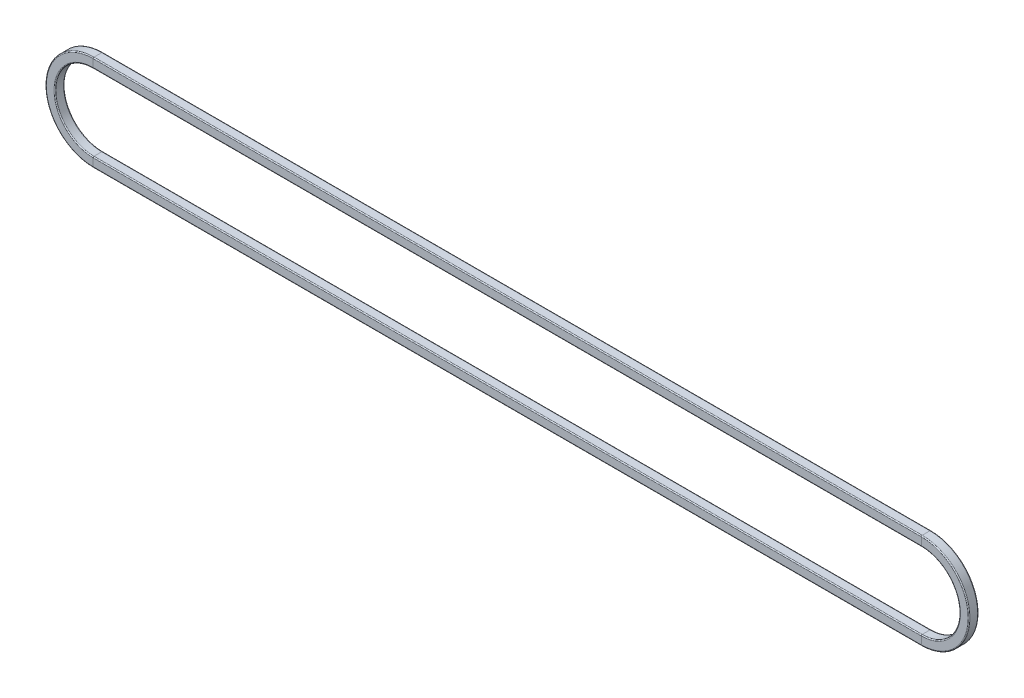
SolidWorks part; units mm, degrees
ref_plane "Front Plane" through (0, 0, 0) normal (0, 0, 1) x (1, 0, 0)
ref_plane "Top Plane" through (0, 0, 0) normal (0, 1, 0) x (1, 0, 0)
ref_plane "Right Plane" through (0, 0, 0) normal (1, 0, 0) x (0, 0, -1)
sketch "Sketch2" plane through (0, 0, 0) normal (0, 0, 1) x (1, 0, 0)
  line L0 (0, 0) -> (1, 0) construction
  line L1 (0, 0) -> (0, 1) construction
  line L2 (0, 4.5) -> (86.8, 4.5)
  line L3 (86.8, -4.5) -> (0, -4.5)
  arc A0 (0, -4.5) -> (0, 4.5) centre (0, 0) cw
  arc A1 (86.8, 4.5) -> (86.8, -4.5) centre (86.8, 0) cw
sketch "Sketch3" plane through (0, 0, 0) normal (1, 0, 0) x (0, 0, -1)
  line L0 (0, 4.5) -> (0, -4.5) construction
  line L1 (-0.5, 5) -> (0.5, 5)
  line L2 (-0.5, 5) -> (-0.5, 4)
  line L3 (-0.5, 4) -> (0.5, 4)
  line L4 (0.5, 5) -> (0.5, 4)
  line L5 (-0.5, 5) -> (0.5, 4) construction
  line L6 (-0.5, 4) -> (0.5, 5) construction
  point P0 (0, 4.5)
  dimension "D1" = 1
  dimension "D2" = 1
  dimension "D3" = 4.5
sweep "rubber_band" add profiles "Sketch3" path "Sketch2"
fillet "soft_edges" radius 0.1 16 edges at (90.8, 0, -0.5) (43.4, -4, -0.5) (-4, 0, -0.5) (90.8, 0, 0.5) (43.4, -4, 0.5) (-4, 0, 0.5) (91.8, 0, 0.5) (43.4, -5, 0.5) (-5, 0, 0.5) (91.8, 0, -0.5) (43.4, -5, -0.5) (-5, 0, -0.5) (43.4, 4, -0.5) (43.4, 4, 0.5) (43.4, 5, 0.5) (43.4, 5, -0.5)
